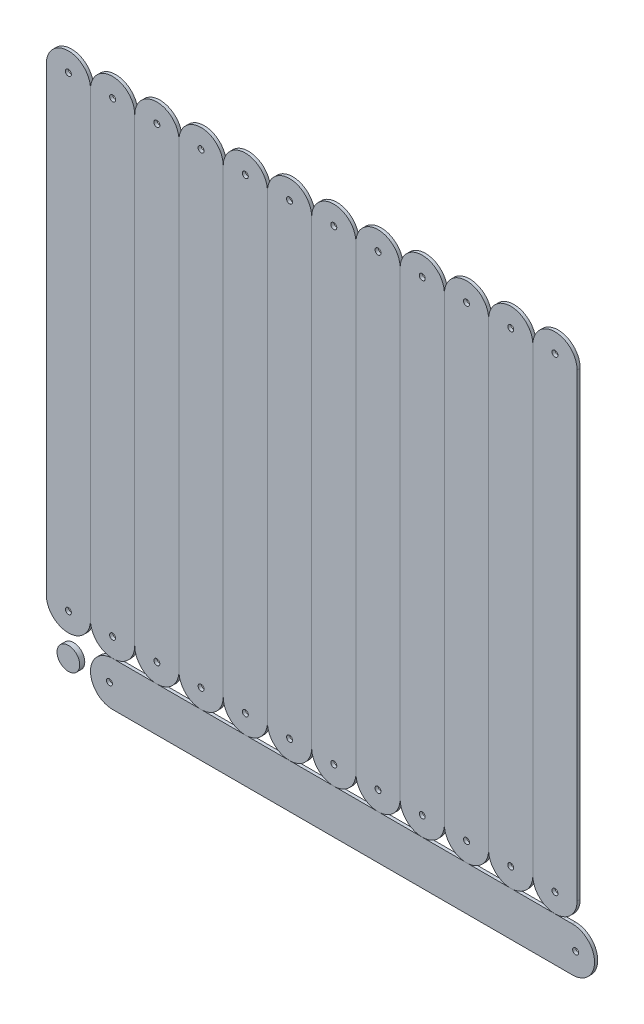
SolidWorks part; units mm, degrees
material "Thornel Mat VMA"
ref_plane "Front Plane" through (0, 0, 0) normal (0, 0, 1) x (1, 0, 0)
ref_plane "Top Plane" through (0, 0, 0) normal (0, 1, 0) x (1, 0, 0)
ref_plane "Right Plane" through (0, 0, 0) normal (1, 0, 0) x (0, 0, -1)
sketch "Sketch1" plane through (0, 0, 0) normal (0, 0, 1) x (1, 0, 0)
  line L0 (0, 115.5186) -> (0, -115.5186) construction
  line L1 (-11.1125, 115.5186) -> (11.1125, 115.5186)
  line L2 (-11.1125, 115.5186) -> (-11.1125, -115.5186)
  line L3 (-11.1125, -115.5186) -> (11.1125, -115.5186)
  line L4 (11.1125, 115.5186) -> (11.1125, -115.5186)
  arc A0 (-11.1125, 115.5186) -> (11.1125, 115.5186) centre (0, 115.5186) cw
  arc A1 (-11.1125, -115.5186) -> (11.1125, -115.5186) centre (0, -115.5186) ccw
  circle A2 centre (0, -117.1061) radius 1.5
  circle A3 centre (0, 117.1061) radius 1.5
  point P10 (0, 126.6311)
  point P11 (0, -126.6311)
  point P14 (0, 0)
  dimension "D2" = 253.2621
  dimension "D5" = 3
  dimension "D6" = 3
  dimension "D1" = 22.225
  dimension "D3" = 9.525
  dimension "D4" = 9.525
extrude "Boss-Extrude1" add sketch "Sketch1" along normal blind 1.5875 contours A0 L1 A3 | L1 L0 L3 L4 | L0 L1 L2 L3 | L3 A1 A2
pattern_linear "LPattern1" count 12 spacing 22.225 along (1, 0, 0) of bodies 101
sketch "Sketch2" plane through (0, 0, 1.5875) normal (0, 0, 1) x (1, 0, 0)
  line L1 (-11.1125, 126.6311) -> (268.2875, 126.6311)
  line L2 (-11.1125, 126.6311) -> (-11.1125, -152.7689)
  line L3 (-11.1125, -152.7689) -> (268.2875, -152.7689)
  line L4 (268.2875, 126.6311) -> (268.2875, -152.7689)
  dimension "D1" = 279.4
  dimension "D2" = 279.4
sketch "Sketch3" plane through (0, 0, 1.5875) normal (0, 0, 1) x (1, 0, 0)
  arc A0 (-11.1125, -115.5186) -> (11.1125, -115.5186) centre (0, -115.5186) ccw construction
  circle A1 centre (0, -137.7436) radius 5.6977
  point P0 (0, -137.7436)
  dimension "D1" = 22.225
extrude "Boss-Extrude2" add sketch "Sketch3" against normal blind 2.54 separate body contours A1
pattern_circular "CirPattern1" count 2 every 90 about axis through (0, -137.7436, 0) along (0, 0, 1) of bodies 101
